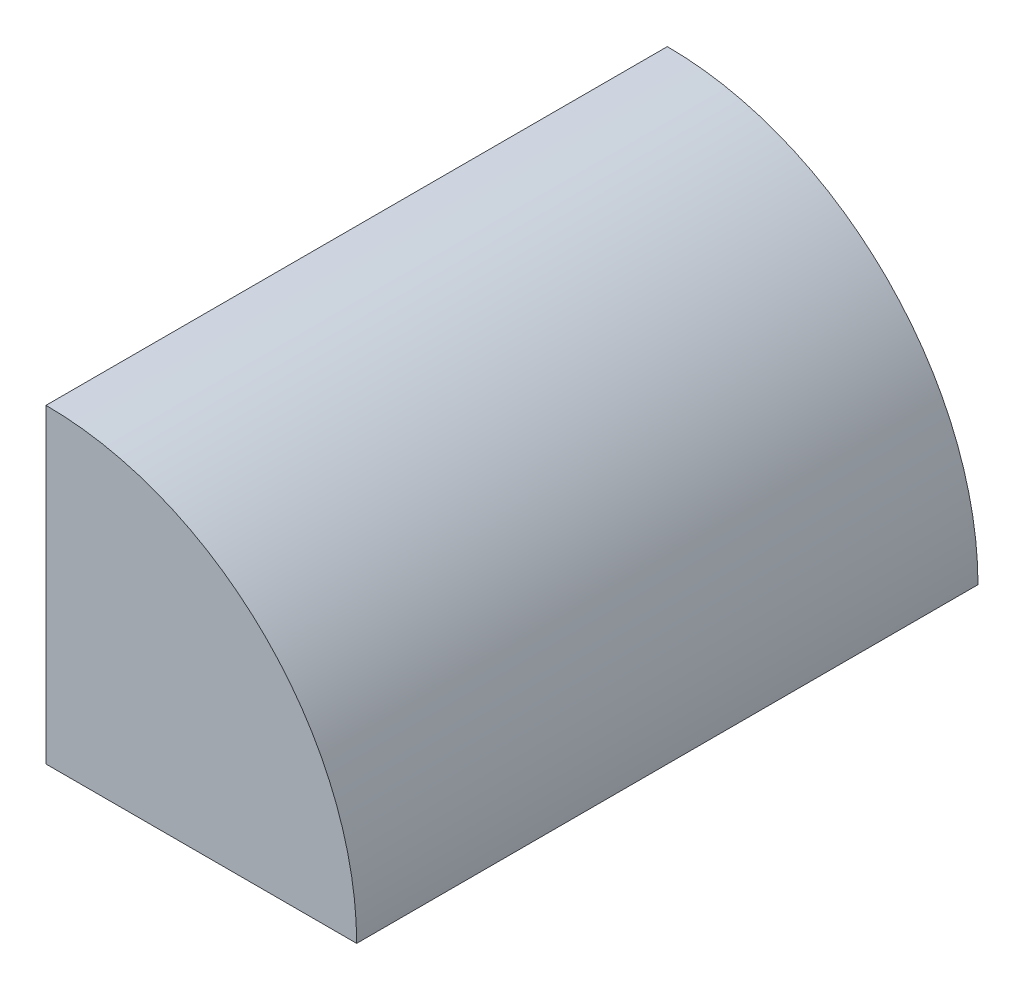
SolidWorks part; units mm, degrees
ref_plane "Alzado" through (0, 0, 0) normal (0, 0, 1) x (1, 0, 0)
ref_plane "Planta" through (0, 0, 0) normal (0, 1, 0) x (1, 0, 0)
ref_plane "Vista lateral" through (0, 0, 0) normal (1, 0, 0) x (0, 0, -1)
sketch "Croquis1" plane through (0, 0, 0) normal (0, 0, 1) x (1, 0, 0)
  line L0 (0, 25) -> (0, 0)
  line L1 (0, 0) -> (25, 0)
  arc A0 (25, 0) -> (0, 25) centre (0, 0) ccw
  dimension "D1" = 50
extrude "Saliente-Extruir1" add sketch "Croquis1" along normal blind 50
sketch "Croquis2" plane through (0, 0, 0) normal (0, 0, -1) x (-1, 0, 0)
  circle A0 centre (-10.8222, 9.6915) radius 5
  dimension "D1" = 10
extrude "Cortar-Extruir1" cut sketch "Croquis2" against normal blind 10
